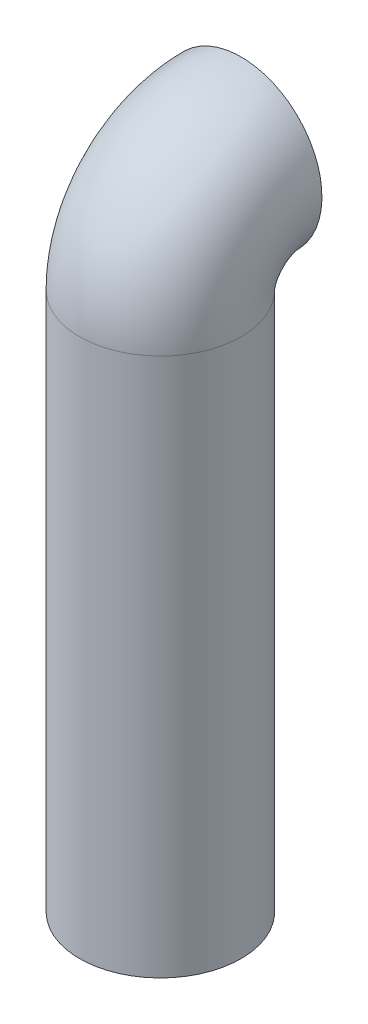
SolidWorks part; units mm, degrees
ref_plane "Front Plane" through (0, 0, 0) normal (0, 0, 1) x (1, 0, 0)
ref_plane "Top Plane" through (0, 0, 0) normal (0, 1, 0) x (1, 0, 0)
ref_plane "Right Plane" through (0, 0, 0) normal (1, 0, 0) x (0, 0, -1)
sketch "Sketch1" plane through (0, 0, 0) normal (1, 0, 0) x (0, 0, -1)
  arc A0 (0, 45) -> (-45, 0) centre (0, 0) ccw
  dimension "D1" = 45
sketch "Sketch2" plane through (0, 0, 0) normal (0, 1, 0) x (1, 0, 0)
  line L0 (0, -45) -> (0, 0) construction
  circle A0 centre (0, -45) radius 45
  dimension "D1" = 90
  dimension "D2" = 45
sweep "Sweep1" add profiles "Sketch2" path "Sketch1"
sketch "Sketch3" plane through (0, 0, 0) normal (0, 0, -1) x (-1, 0, 0)
  line L0 (0, 45) -> (0, 0) construction
  circle A0 centre (0, 45) radius 10
  dimension "D1" = 20
extrude "Cut-Extrude1" cut sketch "Sketch3" against normal blind 20
sketch "Sketch4" plane through (0, 0, 0) normal (0, -1, 0) x (1, 0, 0)
  circle A0 centre (0, 45) radius 45
extrude "Boss-Extrude1" add sketch "Sketch4" along normal blind 300
sketch "Sketch5" plane through (0, -300, 0) normal (0, -1, 0) x (1, 0, 0)
  circle A0 centre (0, 45) radius 10
  dimension "D1" = 20
extrude "Cut-Extrude2" cut sketch "Sketch5" against normal blind 20
ref_point "Point1"
sketch "Sketch6" plane through (0, 0, 0) normal (0, 0, -1) x (-1, 0, 0)
  line L0 (0, 45) -> (63.3375, 45) construction
  line L1 (63.3375, 45) -> (63.3375, 19.7381) construction
